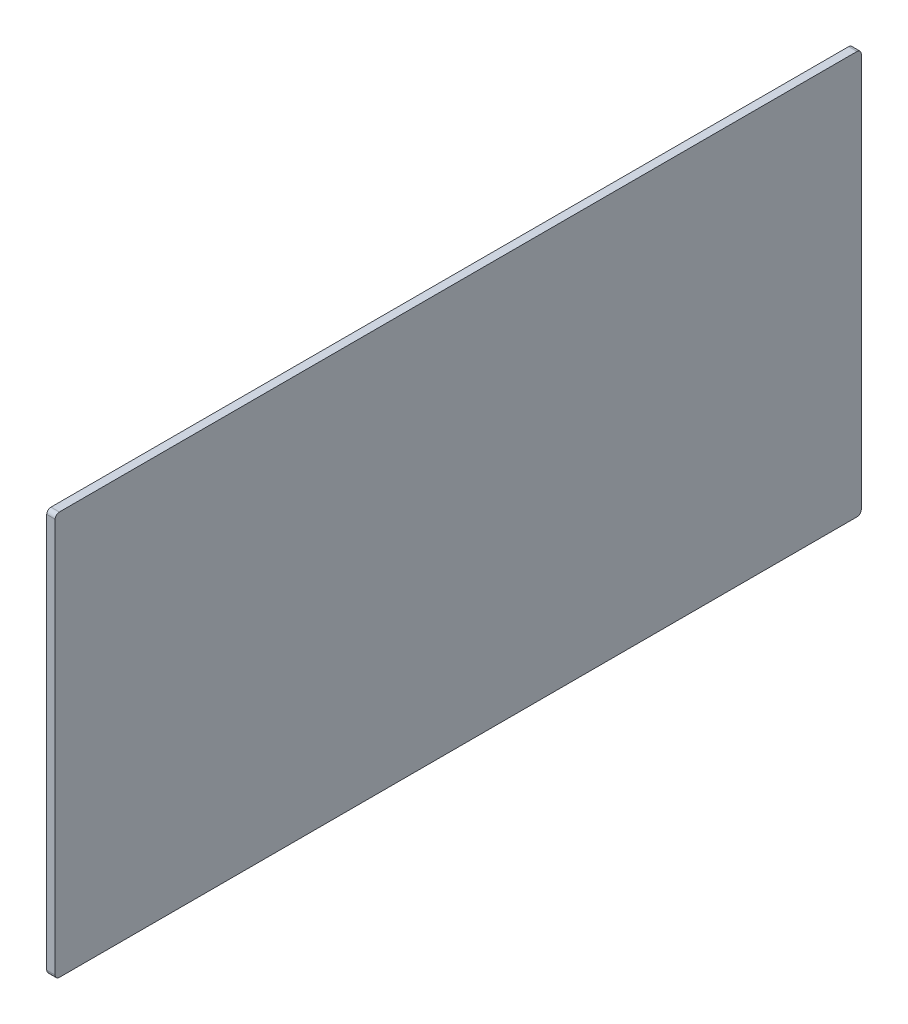
SolidWorks part; units mm, degrees
ref_plane "Front Plane" through (0, 0, 0) normal (0, 0, 1) x (1, 0, 0)
ref_plane "Top Plane" through (0, 0, 0) normal (0, 1, 0) x (1, 0, 0)
ref_plane "Right Plane" through (0, 0, 0) normal (1, 0, 0) x (0, 0, -1)
sketch "Sketch2" plane through (0, 0, 0) normal (1, 0, 0) x (0, 0, -1)
  line L1 (0, 0) -> (609.6, 0)
  line L2 (0, 0) -> (0, 304.8)
  line L3 (0, 304.8) -> (609.6, 304.8)
  line L4 (609.6, 0) -> (609.6, 304.8)
  dimension "D1" = 609.6
  dimension "D2" = 304.8
extrude "Boss-Extrude1" add sketch "Sketch2" along normal blind 6.35
fillet "Fillet1" radius 3.175 4 edges at (3.175, 304.8, -609.6) (3.175, 0, -609.6) (3.175, 0, 0) (3.175, 304.8, 0)
